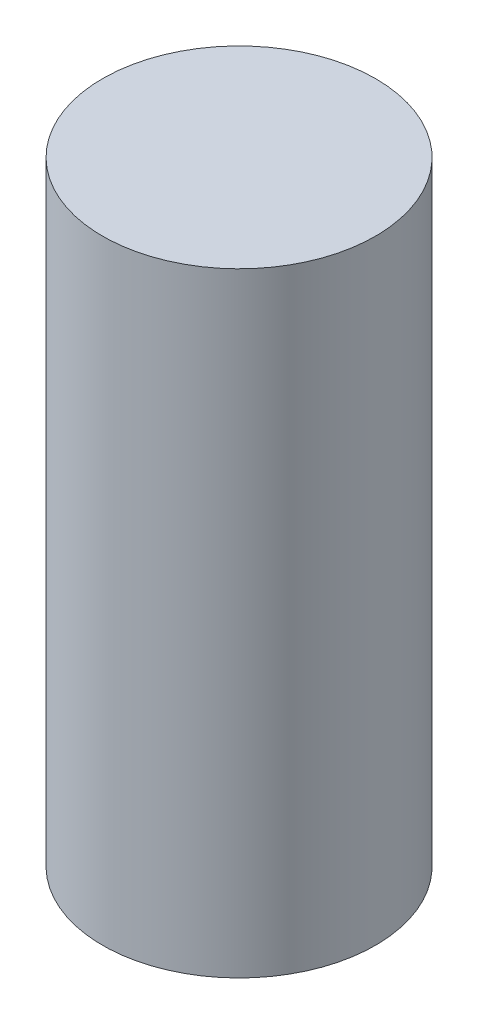
SolidWorks part; units mm, degrees
ref_plane "Front Plane" through (0, 0, 0) normal (0, 0, 1) x (1, 0, 0)
ref_plane "Top Plane" through (0, 0, 0) normal (0, 1, 0) x (1, 0, 0)
ref_plane "Right Plane" through (0, 0, 0) normal (1, 0, 0) x (0, 0, -1)
sketch "Sketch1" plane through (0, 0, 0) normal (0, 1, 0) x (1, 0, 0)
  circle A0 centre (0, 0) radius 40
  dimension "D1" = 80
extrude "Boss-Extrude1" add sketch "Sketch1" along normal blind 180
